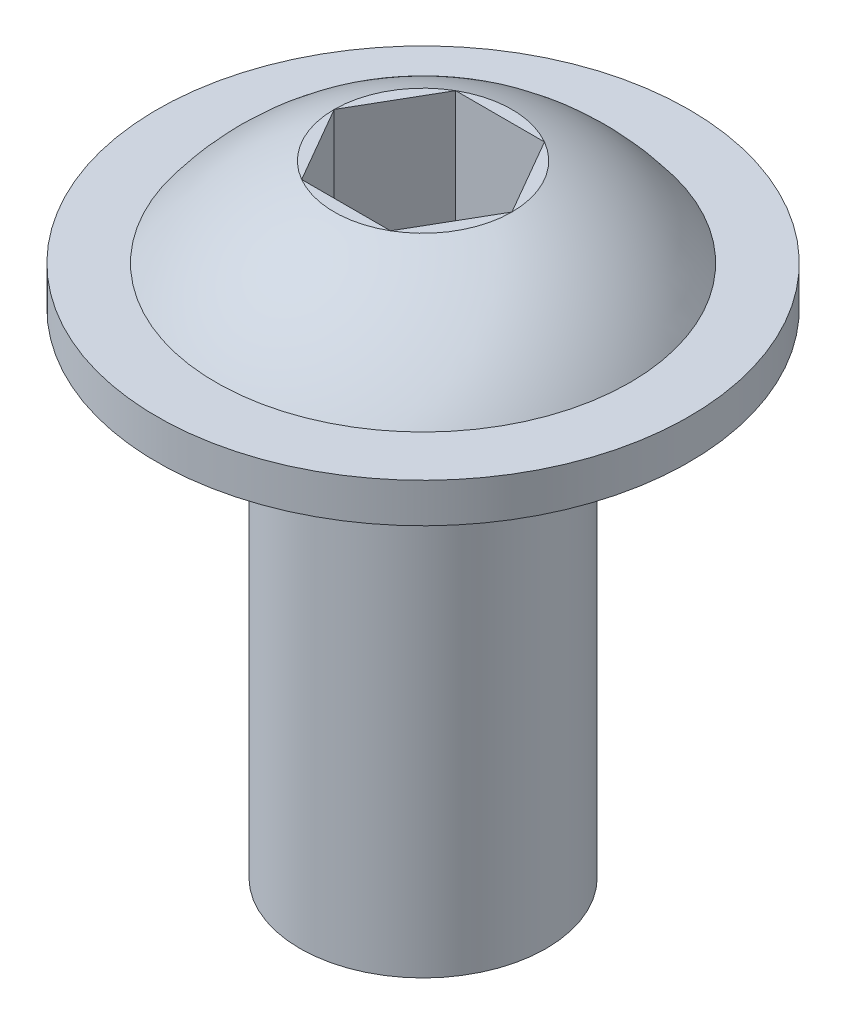
SolidWorks part; units mm, degrees
ref_plane "Front"
ref_plane "Top" through (0, 0, 0) normal (0, 1, 0) x (1, 0, 0)
ref_plane "Right" through (0, 0, 0) normal (1, 0, 0) x (0, 0, -1)
sketch "Sketch1" plane through (0, 0, 0) normal (0, 0, 1) x (1, 0, 0)
  line L0 (0, 0) -> (3.175, 0)
  line L1 (3.175, 0) -> (3.175, 12.7)
  line L2 (3.175, 12.7) -> (6.858, 12.7)
  line L3 (6.858, 12.7) -> (6.858, 13.716)
  line L4 (6.858, 13.716) -> (5.334, 13.716)
  line L5 (0, 0) -> (0, 16.002)
  line L6 (0, 0) -> (0, 30.7805) construction
  line L8 (2.2914, 16.002) -> (0, 16.002)
  arc A0 (5.334, 13.716) -> (2.2914, 16.002) centre (0, 9.7844) ccw
  dimension "MajorDia" = 6.35
  dimension "D2" = 4.5827
  dimension "Length" = 12.7
  dimension "FlangeThick" = 1.016
  dimension "FlangeDiam" = 13.716
  dimension "HeadHeight" = 3.302
  dimension "HeadDiam" = 10.668
revolve "Screw revolve" add sketch "Sketch1" angle 360 about L6
sketch "Sketch2" plane through (0, 16.002, 0) normal (0, 1, 0) x (-1, 0, 0)
  line L1 (-2.2914, 0) -> (-1.1457, -1.9844)
  line L2 (-1.1457, -1.9844) -> (1.1457, -1.9844)
  line L3 (1.1457, -1.9844) -> (2.2914, 0)
  line L4 (2.2914, 0) -> (1.1457, 1.9844)
  line L5 (1.1457, 1.9844) -> (-1.1457, 1.9844)
  line L6 (-1.1457, 1.9844) -> (-2.2914, 0)
  circle A0 centre (0, 0) radius 1.9844 construction
  dimension "D1" = 4.5827
  dimension "HexWidth" = 3.9688
extrude "Hex Cut" cut sketch "Sketch2" against normal blind 3.175
equation "\"D2@Sketch1\" = \"D1@Sketch2\""
